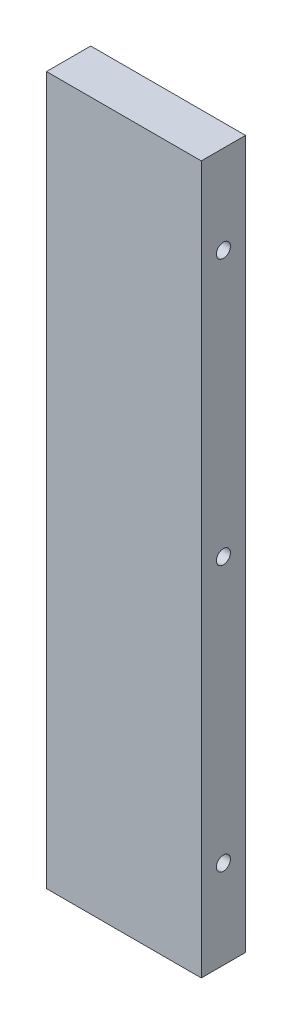
SolidWorks part; units mm, degrees
material "6061-T6 (SS)"
ref_plane "Front Plane" through (0, 0, 0) normal (0, 0, 1) x (1, 0, 0)
ref_plane "Top Plane" through (0, 0, 0) normal (0, 1, 0) x (1, 0, 0)
ref_plane "Right Plane" through (0, 0, 0) normal (1, 0, 0) x (0, 0, -1)
sketch "Sketch1" plane through (0, 0, 0) normal (0, 0, 1) x (1, 0, 0)
  line L1 (-44.45, -78.28) -> (0, -78.28)
  line L2 (-44.45, -78.28) -> (-44.45, 124.92)
  line L3 (-44.45, 124.92) -> (0, 124.92)
  line L4 (0, -78.28) -> (0, 124.92)
  dimension "D1" = 44.45
  dimension "D2" = 203.2
extrude "Boss-Extrude1" add sketch "Sketch1" along normal blind 12.7
sketch "Sketch2" plane through (0, 0, 12.7) normal (0, 0, 1) x (1, 0, 0)
  circle A0 centre (-22.225, 108.41) radius 3.9624
  circle A1 centre (-22.225, -61.77) radius 3.9624
  dimension "D3" = 170.18
  dimension "D6" = 7.9248
  dimension "D7" = 7.9248
  dimension "D1" = 16.51
  dimension "D2" = 22.225
  dimension "D4" = 16.51
  dimension "D5" = 22.225
sketch "Sketch3" plane through (0, 0, 0) normal (1, 0, 0) x (0, 0, -1)
  circle A0 centre (-6.35, 99.52) radius 1.9812
  circle A1 centre (-6.35, 23.32) radius 1.9812
  circle A2 centre (-6.35, -52.88) radius 1.9812
  dimension "D7" = 3.9624
  dimension "D8" = 3.9624
  dimension "D9" = 3.9624
  dimension "D1" = 25.4
  dimension "D2" = 6.35
  dimension "D3" = 76.2
  dimension "D4" = 25.4
  dimension "3" = 76.2
  dimension "D5" = 6.35
  dimension "D6" = 6.35
hole_wizard "#10-32 Tapped Hole1" positions "Sketch5" profile "Sketch4" tap size "#10-32" standard "ANSI Inch" end condition through all
sketch "Sketch5" plane through (0, 0, 0) normal (1, 0, 0) x (0, 0, -1)
  point P0 (-6.35, 99.52)
  point P3 (-6.35, 23.32)
  point P6 (-6.35, -52.88)
sketch "Sketch4" plane through (0, 99.52, 6.35) normal (0, 1, 0) x (0, 0, -1)
  line L0 (0, 0) -> (0, 44.45)
  line L1 (0, 44.45) -> (2.0193, 44.45)
  line L2 (2.0193, 44.45) -> (2.0193, 0)
  line L5 (2.0193, 0) -> (0, 0)
  line L11 (0, -6.35) -> (0, 107.95) construction
  dimension "Thru Tap Drill Dia." = 4.0386
  dimension "Thru Tap Drill Depth" = 44.45
cosmetic thread "Hole Thread1" parameters "D2"=4.826
cosmetic thread "Hole Thread2" parameters "D2"=4.826
cosmetic thread "Hole Thread3" parameters "D2"=4.826
